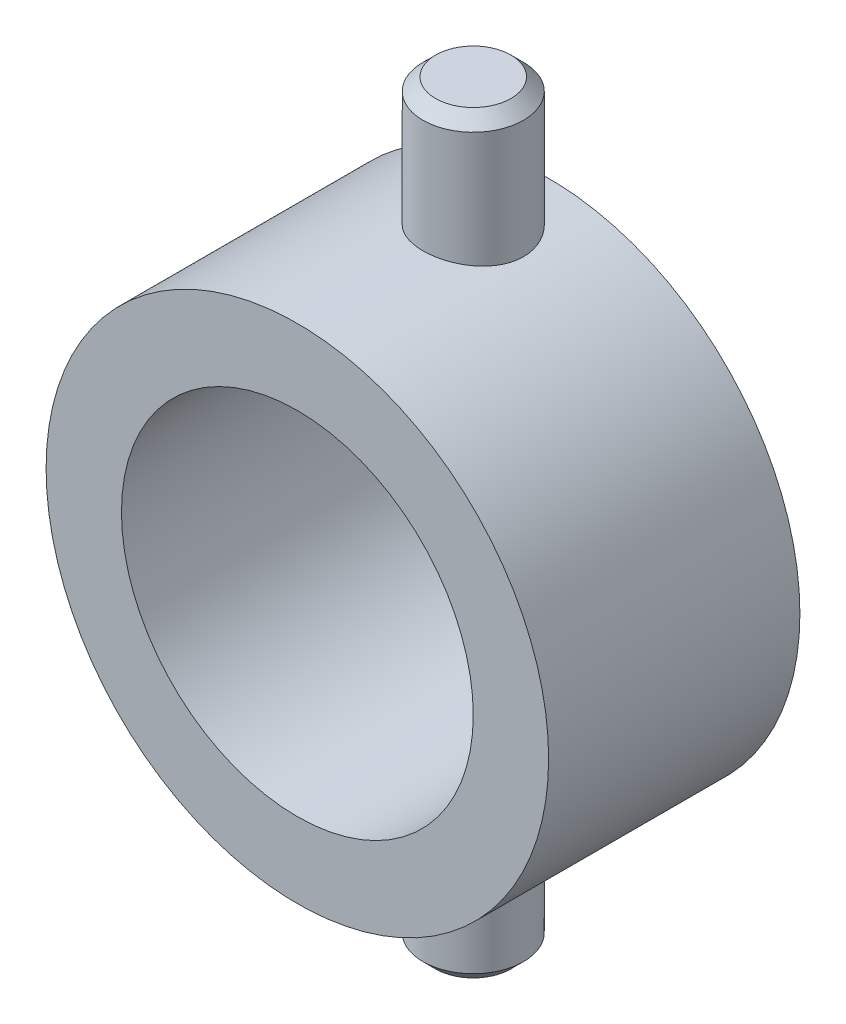
SolidWorks part; units mm, degrees
material "PBT General Purpose"
ref_plane "Front" through (0, 0, 0) normal (0, 0, 1) x (1, 0, 0)
ref_plane "Top" through (0, 0, 0) normal (0, 1, 0) x (1, 0, 0)
ref_plane "Right" through (0, 0, 0) normal (1, 0, 0) x (0, 0, -1)
sketch "Sketch1" plane through (0, 0, 0) normal (0, 0, 1) x (1, 0, 0)
  circle A0 centre (0, 0) radius 10
  dimension "D1" = 20
extrude "Boss-Extrude1" add sketch "Sketch1" along normal blind 10
sketch "Sketch2" plane through (0, 0, 0) normal (0, 0, -1) x (-1, 0, 0)
  circle A0 centre (0, 0) radius 7
  dimension "D1" = 14
extrude "Cut-Extrude1" cut sketch "Sketch2" against normal through all
ref_plane "Plane2" through (0, 15, 0) normal (0, 1, 0) x (1, 0, 0)
sketch "Sketch4" plane through (0, 15, 0) normal (0, 1, 0) x (1, 0, 0)
  line L0 (10, 0) -> (-10, 0) construction
  circle A0 centre (0, -3) radius 2
  dimension "D1" = 4
  dimension "D2" = 3
extrude "Boss-Extrude3" add sketch "Sketch4" against normal up to surface (5 mm away)
mirror "Mirror2" about plane through (0, 0, 0) normal (0, 1, 0) of "Boss-Extrude3"
chamfer "Chamfer2" distance 0.5 angle 45 2 edges at (0, -15, 5) (0, 15, 5)
